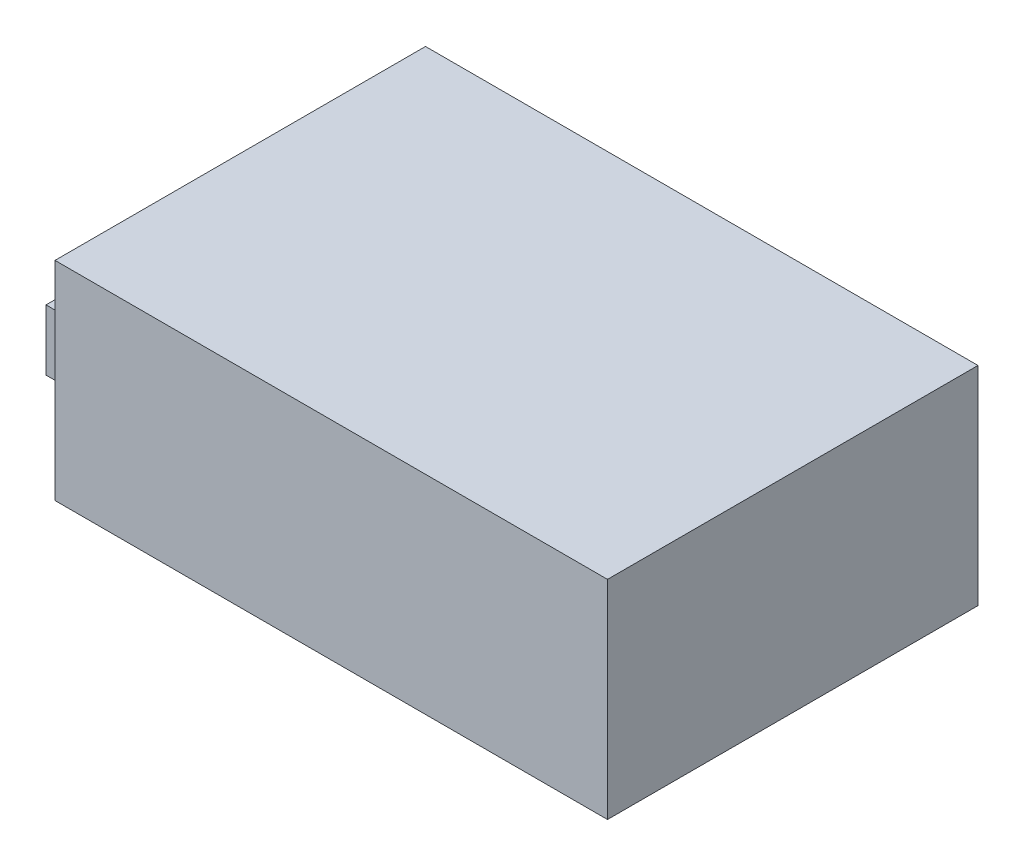
SolidWorks part; units mm, degrees
material "1060 Сплав"
ref_plane "Спереди" through (0, 0, 0) normal (0, 0, 1) x (1, 0, 0)
ref_plane "Сверху" through (0, 0, 0) normal (0, 1, 0) x (1, 0, 0)
ref_plane "Справа" through (0, 0, 0) normal (1, 0, 0) x (0, 0, -1)
sketch "Эскиз1" plane through (0, 0, 0) normal (0, 1, 0) x (1, 0, 0)
  line L1 (42.5, -28.5) -> (-42.5, -28.5)
  line L2 (42.5, -28.5) -> (42.5, 28.5)
  line L3 (42.5, 28.5) -> (-42.5, 28.5)
  line L4 (-42.5, -28.5) -> (-42.5, 28.5)
  line L5 (42.5, -28.5) -> (-42.5, 28.5) construction
  line L6 (42.5, 28.5) -> (-42.5, -28.5) construction
  point P0 (0, 0)
  dimension "D1" = 85
  dimension "D2" = 57
extrude "Бобышка-Вытянуть1" add sketch "Эскиз1" along normal blind 32
hole_wizard "Отверстие обработанное метчиком M31" [suppressed] positions "Эскиз2" profile "Эскиз3" tap size "M3" standard "ISO"
sketch "Эскиз2" plane through (0, 0, 28.5) normal (0, 0, 1) x (1, 0, 0)
  line L0 (-42.5, 0) -> (42.5, 0) construction
  line L1 (42.5, 32) -> (42.5, 0) construction
  point P0 (39.75, 14)
  point P2 (-26.75, 14)
  dimension "D1" = 14
  dimension "D2" = 2.75
  dimension "D3" = 66.5
sketch "Эскиз3" plane through (39.75, 14, 28.5) normal (1, 0, 0) x (0, -1, 0)
  line L0 (0, 0) -> (0, 6.2511)
  line L1 (0, 6.2511) -> (1.25, 5.5)
  line L2 (1.25, 5.5) -> (1.25, 0)
  line L5 (1.25, 0) -> (0, 0)
  line L10 (0, 6.2511) -> (-1.25, 5.5) construction
  line L11 (0, -6.35) -> (0, 107.95) construction
  dimension "Диаметр сверла" = 2.5
  dimension "Глубина сверла" = 5.5
  dimension "Угол заточки сверла" = 118
cosmetic thread "Отверстие резьбы1" [suppressed] parameters "D1"=3, "D2"=3
cosmetic thread "Отверстие резьбы2" [suppressed] parameters "D1"=3, "D2"=3
hole_wizard "Отверстие обработанное метчиком M32" [suppressed] positions "Эскиз4" profile "Эскиз5" tap size "M3" standard "ISO"
sketch "Эскиз4" plane through (0, 0, 0) normal (0, -1, 0) x (-1, 0, 0)
  line L1 (42.5, -28.5) -> (-42.5, -28.5) construction
  line L2 (-42.5, -28.5) -> (-42.5, 28.5) construction
  point P0 (-31.5, -3.1)
  point P2 (23.5, -3.1)
  dimension "D1" = 25.4
  dimension "D2" = 11
  dimension "D3" = 55
sketch "Эскиз5" plane through (31.5, 0, 3.1) normal (1, 0, 0) x (0, 0, -1)
  line L0 (0, 0) -> (0, 6.2511)
  line L1 (0, 6.2511) -> (1.25, 5.5)
  line L2 (1.25, 5.5) -> (1.25, 0)
  line L5 (1.25, 0) -> (0, 0)
  line L10 (0, 6.2511) -> (-1.25, 5.5) construction
  line L11 (0, -6.35) -> (0, 107.95) construction
  dimension "Диаметр сверла" = 2.5
  dimension "Глубина сверла" = 5.5
  dimension "Угол заточки сверла" = 118
cosmetic thread "Отверстие резьбы3" [suppressed] parameters "D1"=3, "D2"=3
cosmetic thread "Отверстие резьбы4" [suppressed] parameters "D1"=3, "D2"=3
sketch "Эскиз6" plane through (-42.5, 0, 0) normal (-1, 0, 0) x (0, 0, 1)
  line L1 (-20.6708, 3.4016) -> (15.8844, 3.4016)
  line L2 (-20.6708, 3.4016) -> (-20.6708, 12.764)
  line L3 (-20.6708, 12.764) -> (15.8844, 12.764)
  line L4 (15.8844, 3.4016) -> (15.8844, 12.764)
  line L5 (-2.3932, 12.764) -> (-2.3932, 3.4016) construction
  line L6 (-20.6708, 8.0828) -> (15.8844, 8.0828) construction
  point P220 (-2.3932, 8.0828)
extrude "Бобышка-Вытянуть2" add sketch "Эскиз6" along normal blind 14
